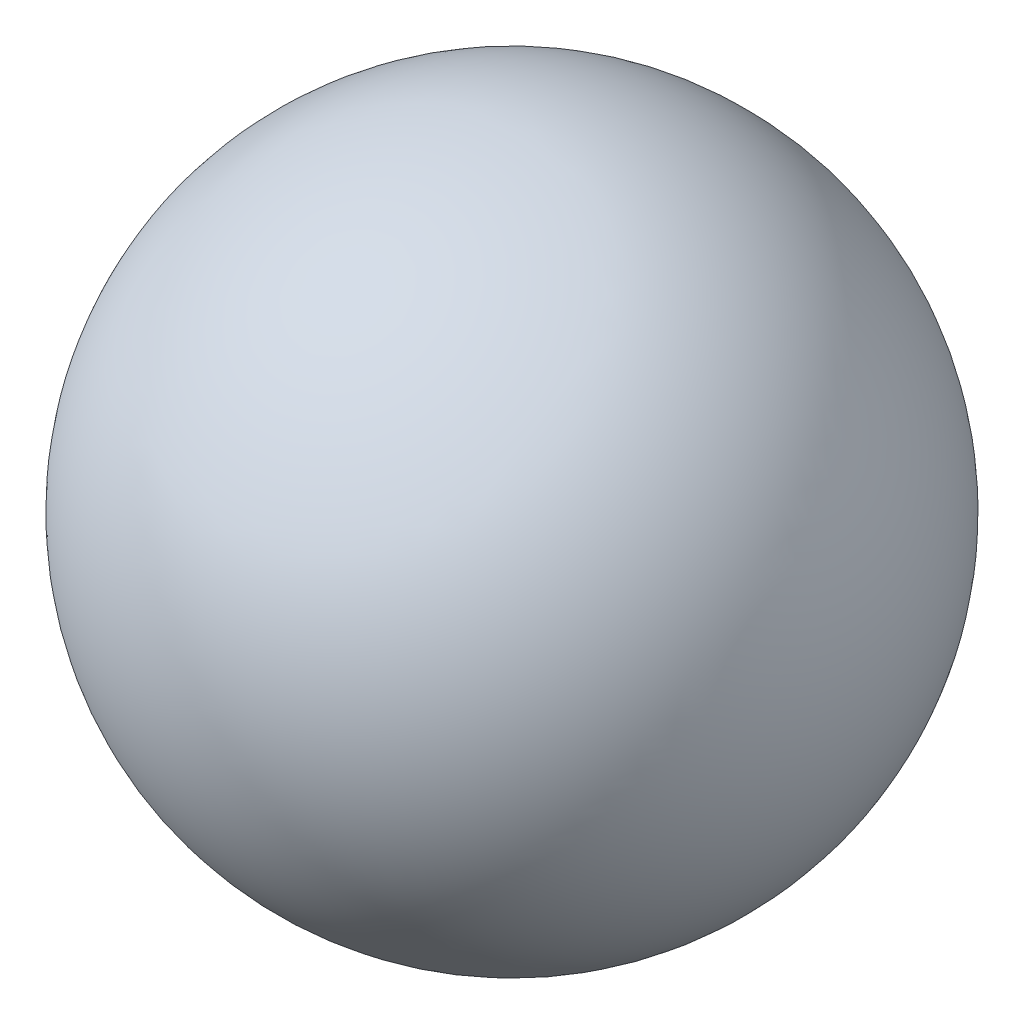
SolidWorks part; units mm, degrees
ref_plane "Front Plane" through (0, 0, 0) normal (0, 0, 1) x (1, 0, 0)
ref_plane "Top Plane" through (0, 0, 0) normal (0, 1, 0) x (1, 0, 0)
ref_plane "Right Plane" through (0, 0, 0) normal (1, 0, 0) x (0, 0, -1)
sketch "Sketch1" plane through (0, 0, 0) normal (0, 0, 1) x (1, 0, 0)
  line L0 (-16, 0) -> (16, 0)
  arc A0 (16, 0) -> (-16, 0) centre (0, 0) cw
  dimension "D1" = 16
  dimension "D2" = 32
revolve "Revolve1" add sketch "Sketch1" angle 360 about L0
ref_plane "Ground" through (0, -16, 0) normal (0, -1, 0) x (-1, 0, 0)
